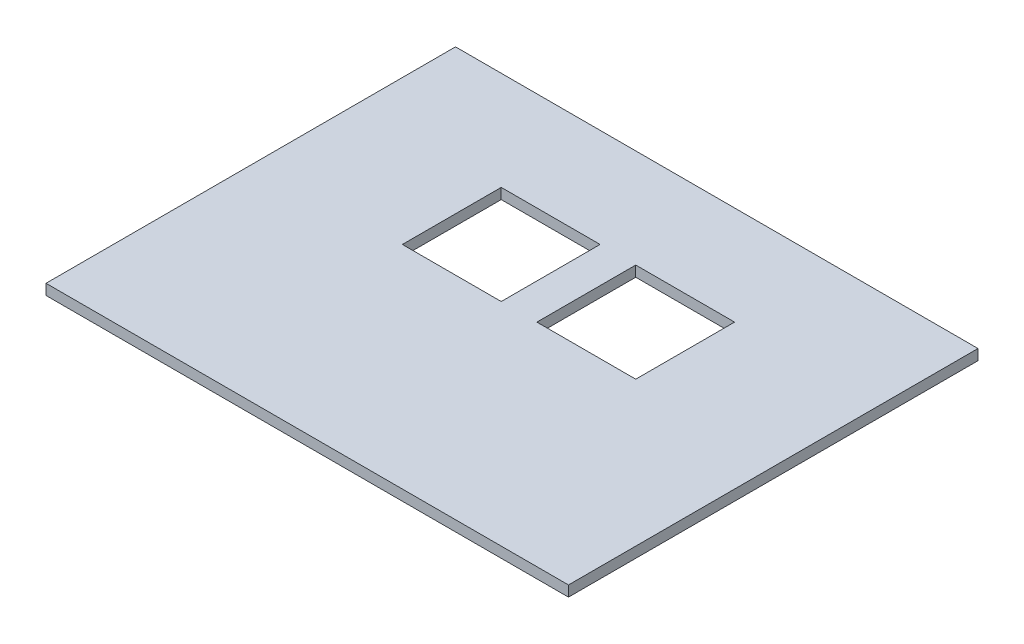
SolidWorks part; units mm, degrees
ref_plane "Ön Düzlem" through (0, 0, 0) normal (0, 0, 1) x (1, 0, 0)
ref_plane "Üst Düzlem" through (0, 0, 0) normal (0, 1, 0) x (1, 0, 0)
ref_plane "Sağ Düzlem" through (0, 0, 0) normal (1, 0, 0) x (0, 0, -1)
sketch "Çizim1" plane through (0, 0, 0) normal (0, 1, 0) x (1, 0, 0)
  line L1 (-37, -29) -> (37, -29)
  line L2 (-37, -29) -> (-37, 29)
  line L3 (-37, 29) -> (37, 29)
  line L4 (37, -29) -> (37, 29)
  line L5 (-37, -29) -> (37, 29) construction
  line L6 (-37, 29) -> (37, -29) construction
  point P0 (0, 0)
  dimension "D1" = 74
  dimension "D2" = 58
extrude "Yükseklik-Ekstrüzyon1" add sketch "Çizim1" along normal blind 1.5
sketch "Çizim2" plane through (0, 0, 0) normal (0, -1, 0) x (1, 0, 0)
  line L0 (-37, 29) -> (37, 29) construction
  line L1 (-34.9, -26.9) -> (34.9, -26.9)
  line L2 (-34.9, -26.9) -> (-34.9, 26.9)
  line L3 (-34.9, 26.9) -> (34.9, 26.9)
  line L4 (34.9, -26.9) -> (34.9, 26.9)
  line L5 (-34.9, -26.9) -> (34.9, 26.9) construction
  line L6 (-34.9, 26.9) -> (34.9, -26.9) construction
  line L7 (-37, -29) -> (-37, 29) construction
  point P0 (0, 0)
  dimension "D1" = 2.1
  dimension "D2" = 2.1
extrude "Ekstrüzyon-İnce1" add sketch "Çizim2" along normal blind 2 thin thin type one direction reverse wall 2
sketch "Çizim4" plane through (0, 1.5, 0) normal (0, 1, 0) x (1, 0, 0)
  line L0 (-37, 29) -> (-37, -29) construction
  line L1 (-16.525, 1) -> (-2.525, 1)
  line L2 (-16.525, 1) -> (-16.525, 15)
  line L3 (-16.525, 15) -> (-2.525, 15)
  line L4 (-2.525, 1) -> (-2.525, 15)
  line L5 (2.525, 1) -> (16.525, 1)
  line L6 (2.525, 1) -> (2.525, 15)
  line L7 (2.525, 15) -> (16.525, 15)
  line L8 (16.525, 1) -> (16.525, 15)
  line L9 (-37, -29) -> (37, -29) construction
  dimension "D1" = 14
  dimension "D2" = 14
  dimension "D3" = 14
  dimension "D4" = 5.05
  dimension "D5" = 20.475
  dimension "D6" = 30
extrude "Kes-Ekstrüzyon4" cut sketch "Çizim4" against normal blind 2
